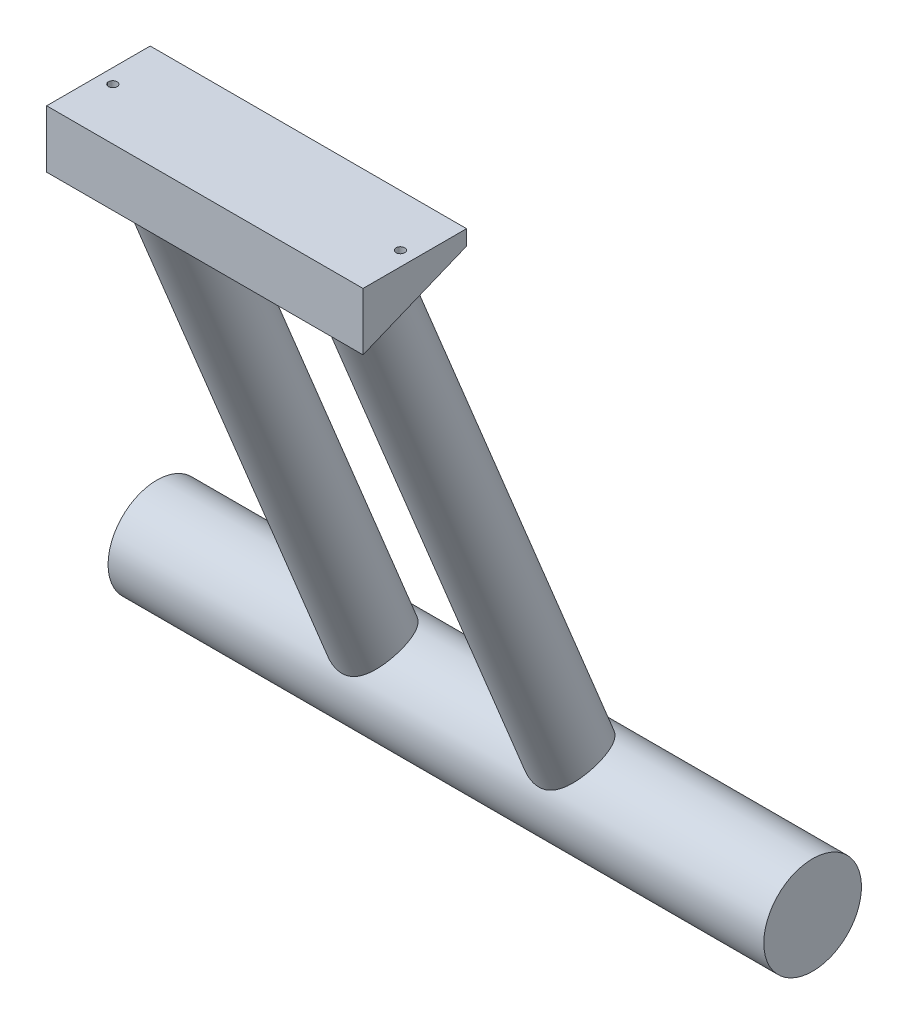
SolidWorks part; units mm, degrees
material "PLA"
ref_plane "Ön Düzlem" through (0, 0, 0) normal (0, 0, 1) x (1, 0, 0)
ref_plane "Üst Düzlem" through (0, 0, 0) normal (0, 1, 0) x (1, 0, 0)
ref_plane "Sağ Düzlem" through (0, 0, 0) normal (1, 0, 0) x (0, 0, -1)
sketch "Çizim1" plane through (0, 0, 0) normal (0, 1, 0) x (1, 0, 0)
  line L0 (0, 0) -> (55, 0)
  line L1 (55, 0) -> (55, -18)
  line L2 (55, -18) -> (0, -18)
  line L3 (0, -18) -> (0, 0)
extrude "Yükseklik-Ekstrüzyon1" add sketch "Çizim1" against normal blind 10
sketch "Çizim2" plane through (0, 0, 0) normal (-1, 0, 0) x (0, 0, 1)
  line L0 (18, -10) -> (0, -2.6307)
  line L1 (0, -10) -> (0, 0) construction
  line L2 (0, -2.6307) -> (0, -10)
  line L3 (0, -10) -> (18, -10)
extrude "Kes-Ekstrüzyon1" cut sketch "Çizim2" against normal through all
sketch "Çizim3" plane through (0, -2.253, -0.9224) normal (0, -0.9254, -0.3789) x (-1, 0, 0)
  line L0 (2.1678, -10.7218) -> (-56.3995, -10.7218) construction
  line L1 (0, -20.4468) -> (0, -0.9967) construction
  circle A0 centre (-10, -10.7218) radius 6
  circle A1 centre (-44.2317, -10.7218) radius 6
  dimension "D1" = 10
extrude "Yükseklik-Ekstrüzyon2" add sketch "Çizim3" along normal blind 100
sketch "Çizim5" plane through (0, -94.7974, -38.8108) normal (0, -0.9254, -0.3789) x (-1, 0, 0)
  line L1 (-4, -4.7218) -> (-16, -4.7218)
  line L2 (-4, -4.7218) -> (-4, -16.7218)
  line L3 (-4, -16.7218) -> (-16, -16.7218)
  line L4 (-16, -4.7218) -> (-16, -16.7218)
  line L5 (-10, -16.7218) -> (-10, -4.7218) construction
  line L6 (-4, -10.7218) -> (-16, -10.7218) construction
  line L7 (-38.2317, -4.7218) -> (-50.2317, -4.7218)
  line L8 (-38.2317, -4.7218) -> (-38.2317, -16.7218)
  line L9 (-38.2317, -16.7218) -> (-50.2317, -16.7218)
  line L10 (-50.2317, -4.7218) -> (-50.2317, -16.7218)
  line L11 (-44.2317, -16.7218) -> (-44.2317, -4.7218) construction
  line L12 (-38.2317, -10.7218) -> (-50.2317, -10.7218) construction
  point P0 (-10, -10.7218)
  point P4 (-44.2317, -10.7218)
extrude "Yükseklik-Ekstrüzyon3" add sketch "Çizim5" along normal blind 12
sketch "Çizim6" plane through (4, 0, 0) normal (-1, 0, 0) x (0, 0, 1)
  circle A0 centre (-31.1617, -104.4124) radius 8.4853
  point P3 (28572.2591, 500000)
sketch "Çizim7" plane through (0, 0, 0) normal (0, 1, 0) x (1, 0, 0)
  circle A0 centre (2.5, -9) radius 0.75
  circle A1 centre (52.5, -9) radius 0.75
  point P4 (0, 0)
extrude "Kes-Ekstrüzyon3" cut sketch "Çizim7" against normal through all
extrude "Yükseklik-Ekstrüzyon4" add sketch "Çizim6" against normal blind 80 and the other way blind 34
